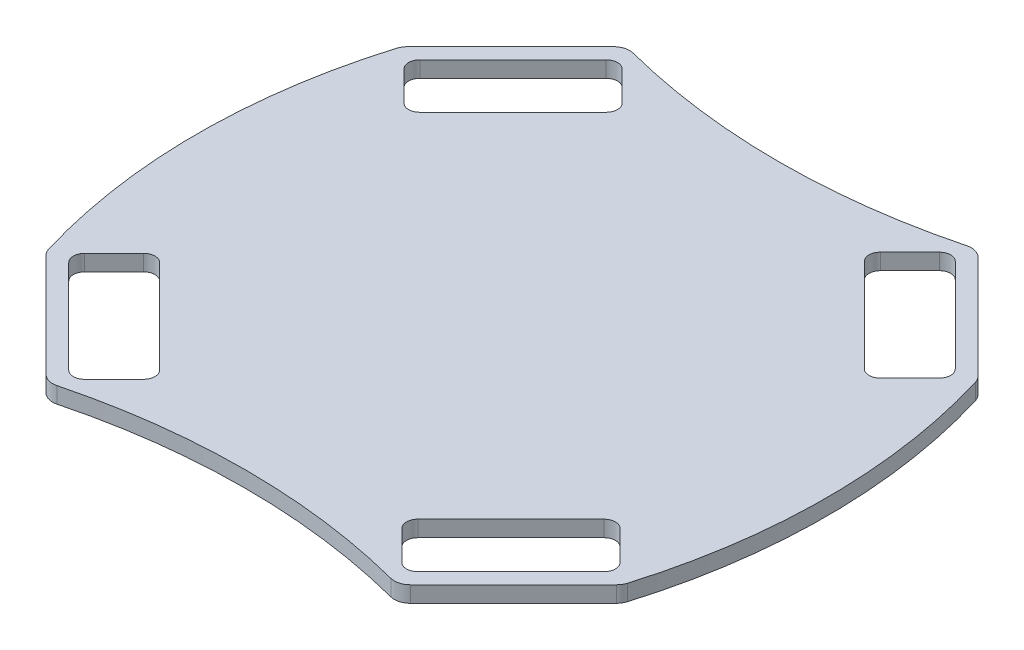
SolidWorks part; units mm, degrees
ref_plane "Plano frontal" through (0, 0, 0) normal (0, 0, 1) x (1, 0, 0)
ref_plane "Plano superior" through (0, 0, 0) normal (0, 1, 0) x (1, 0, 0)
ref_plane "Plano direito" through (0, 0, 0) normal (1, 0, 0) x (0, 0, -1)
sketch "Esboço1" plane through (0, 0, 0) normal (0, 1, 0) x (1, 0, 0)
  line L0 (-50.5427, 81.3827) -> (-18.4437, 113.4817)
  line L1 (-16.7516, 115.1738) -> (-15.1276, 115.1738)
  line L2 (-51.7516, 80.1738) -> (-51.7516, 79.4325)
  line L3 (-16.7516, -64.8262) -> (-15.1276, -64.8262)
  line L4 (128.2484, 80.1738) -> (128.2484, 79.4325)
  line L5 (-50.5427, -31.035) -> (-18.4437, -63.1341)
  line L6 (127.0395, -31.035) -> (94.9405, -63.1341)
  line L7 (94.9405, 113.4817) -> (127.0395, 81.3827)
  line L8 (91.6245, 115.1738) -> (93.2484, 115.1738)
  line L9 (-51.7516, -29.0848) -> (-51.7516, -29.8262)
  line L10 (128.2484, -29.0848) -> (128.2484, -29.8262)
  line L11 (91.6245, -64.8262) -> (93.2484, -64.8262)
  arc A0 (-51.7956, 79.2864) -> (-51.7956, -28.9387) centre (128.2484, 25.1738) ccw
  arc A1 (128.2924, -28.9387) -> (128.2924, 79.2864) centre (-51.7516, 25.1738) ccw
  arc A2 (-13.6544, 114.7865) -> (90.1513, 114.7865) centre (38.2484, 315.1738) ccw
  arc A3 (90.1513, -64.4388) -> (-13.6544, -64.4388) centre (38.2484, -264.8262) ccw
  arc A4 (94.9405, 113.4817) -> (90.1513, 114.7865) centre (91.405, 109.9462) ccw
  arc A5 (94.9405, -63.1341) -> (90.1513, -64.4388) centre (91.405, -59.5985) cw
  arc A6 (-13.6544, -64.4388) -> (-18.4437, -63.1341) centre (-14.9081, -59.5985) cw
  arc A7 (-13.6544, 114.7865) -> (-18.4437, 113.4817) centre (-14.9081, 109.9462) ccw
  arc A8 (128.2924, 79.2864) -> (127.0395, 81.3827) centre (123.504, 77.8472) ccw
  arc A9 (128.2924, -28.9387) -> (127.0395, -31.035) centre (123.504, -27.4995) cw
  arc A10 (-51.7956, -28.9387) -> (-50.5427, -31.035) centre (-47.0072, -27.4995) ccw
  arc A11 (-50.5427, 81.3827) -> (-51.7956, 79.2864) centre (-47.0072, 77.8472) ccw
  point P0 (-51.7516, 115.1738)
  point P1 (128.2484, -64.8262)
  point P2 (-51.7516, -64.8262)
  point P3 (128.2484, 115.1738)
  point P24 (0, 0)
  dimension "D1" = 5
  dimension "D2" = 5
extrude "Ressalto-extrusão2" add sketch "Esboço1" along normal blind 5 contours A3 L11 L6 A1 L7 L8 A2 L1 L0 A0 L5 L3
sketch "Esboço2" plane through (0, 5, 0) normal (0, 1, 0) x (1, 0, 0)
  line L0 (-34.4932, 97.4322) -> (-30.9576, 93.8967) construction
  line L1 (-50.5427, 81.3827) -> (-18.4437, 113.4817) construction
  line L2 (-30.9576, 93.8967) -> (-45.0493, 79.805)
  line L3 (-30.9576, 93.8967) -> (-16.0579, 108.7964)
  line L4 (-11.1082, 108.7964) -> (-1.9158, 99.604)
  line L5 (-45.0493, 74.8553) -> (-35.8569, 65.6629)
  line L6 (-30.9072, 65.6629) -> (-1.9158, 94.6543)
  line L7 (-59.7516, 25.1738) -> (161.9106, 25.1738)
  line L8 (38.2484, 108.1738) -> (38.2484, -57.8262)
  line L9 (-30.9576, -43.549) -> (-16.0579, -58.4487)
  line L10 (-11.1082, -58.4487) -> (-1.9158, -49.2563)
  line L11 (-30.9576, -43.549) -> (-45.0493, -29.4574)
  line L12 (-45.0493, -24.5076) -> (-35.8569, -15.3152)
  line L13 (-30.9072, -15.3152) -> (-1.9158, -44.3066)
  line L14 (107.4545, -43.549) -> (121.5462, -29.4574)
  line L15 (107.4545, -43.549) -> (92.5548, -58.4487)
  line L16 (87.605, -58.4487) -> (78.4126, -49.2563)
  line L17 (121.5462, -24.5076) -> (112.3538, -15.3152)
  line L18 (107.404, -15.3152) -> (78.4126, -44.3066)
  line L19 (87.605, 108.7964) -> (78.4126, 99.604)
  line L20 (107.4545, 93.8967) -> (92.5548, 108.7964)
  line L21 (107.4545, 93.8967) -> (121.5462, 79.805)
  line L22 (107.404, 65.6629) -> (78.4126, 94.6543)
  line L23 (121.5462, 74.8553) -> (112.3538, 65.6629)
  arc A0 (-51.7956, 79.2864) -> (-51.7956, -28.9387) centre (128.2484, 25.1738) ccw construction
  arc A1 (-13.6544, 114.7865) -> (90.1513, 114.7865) centre (38.2484, 315.1738) ccw construction
  arc A2 (90.1513, -64.4388) -> (-13.6544, -64.4388) centre (38.2484, -264.8262) ccw construction
  arc A3 (-1.9158, 94.6543) -> (-1.9158, 99.604) centre (-4.3907, 97.1292) ccw
  arc A4 (-35.8569, 65.6629) -> (-30.9072, 65.6629) centre (-33.382, 68.1378) ccw
  arc A5 (-45.0493, 74.8553) -> (-45.0493, 79.805) centre (-42.5744, 77.3302) cw
  arc A6 (-11.1082, 108.7964) -> (-16.0579, 108.7964) centre (-13.5831, 106.3215) ccw
  arc A7 (-45.0493, 74.8553) -> (-45.0493, 79.805) centre (-42.5744, 77.3302) cw
  arc A8 (-45.0493, 74.8553) -> (-45.0493, 79.805) centre (-42.5744, 77.3302) cw
  arc A9 (78.4126, 99.604) -> (78.4126, 94.6543) centre (80.8875, 97.1292) ccw
  arc A10 (87.605, 108.7964) -> (92.5548, 108.7964) centre (90.0799, 106.3215) cw
  arc A11 (121.5462, 79.805) -> (121.5462, 74.8553) centre (119.0713, 77.3302) cw
  arc A12 (107.404, 65.6629) -> (112.3538, 65.6629) centre (109.8789, 68.1378) ccw
  arc A13 (121.5462, -29.4574) -> (121.5462, -24.5076) centre (119.0713, -26.9825) ccw
  arc A14 (112.3538, -15.3152) -> (107.404, -15.3152) centre (109.8789, -17.7901) ccw
  arc A15 (87.605, -58.4487) -> (92.5548, -58.4487) centre (90.0799, -55.9739) ccw
  arc A16 (78.4126, -49.2563) -> (78.4126, -44.3066) centre (80.8875, -46.7815) cw
  arc A17 (-1.9158, -49.2563) -> (-1.9158, -44.3066) centre (-4.3907, -46.7815) ccw
  arc A18 (-16.0579, -58.4487) -> (-11.1082, -58.4487) centre (-13.5831, -55.9739) ccw
  arc A19 (-45.0493, -24.5076) -> (-45.0493, -29.4574) centre (-42.5744, -26.9825) ccw
  arc A20 (-30.9072, -15.3152) -> (-35.8569, -15.3152) centre (-33.382, -17.7901) ccw
  arc A21 (-30.9072, -15.3152) -> (-35.8569, -15.3152) centre (-33.382, -17.7901) ccw
  point P37 (0, 0)
  point P40 (0.5591, 97.1292)
  point P43 (-33.382, 63.188)
  point P46 (-47.5242, 77.3302)
  point P49 (-13.5831, 111.2713)
  point P56 (75.9378, 97.1292)
  point P59 (90.0799, 111.2713)
  point P62 (124.021, 77.3302)
  point P65 (109.8789, 63.188)
  point P68 (124.021, -26.9825)
  point P71 (109.8789, -12.8403)
  point P74 (90.0799, -60.9236)
  point P77 (75.9378, -46.7815)
  point P80 (0.5591, -46.7815)
  point P83 (-13.5831, -60.9236)
  point P86 (-47.5242, -26.9825)
  point P89 (-33.382, -12.8403)
  dimension "D1" = 3.5
  dimension "D2" = 3.5
  dimension "D3" = 3.5
  dimension "D4" = 3.5
  dimension "D5" = 3.5
extrude "Corte-extrusão1" cut sketch "Esboço2" against normal blind 5 contours L5 L6 L4 L3 L2 | L13 L12 L11 L9 L10 | L17 L18 L16 L15 L14 | L23 L21 L20 L19 L22
